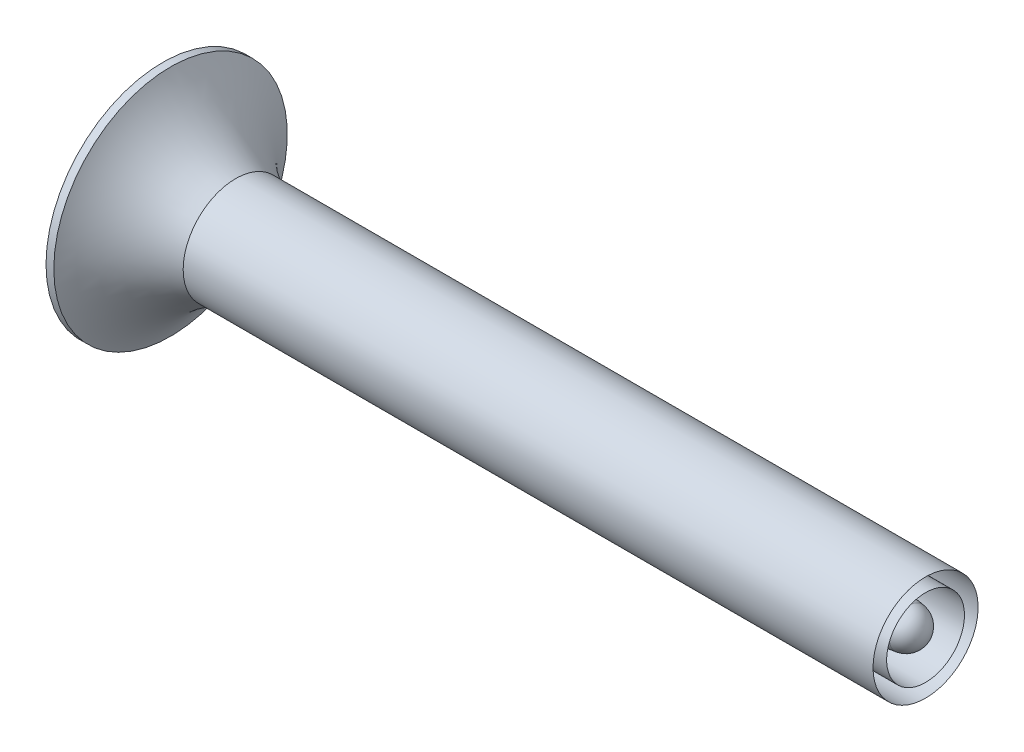
SolidWorks part; units mm, degrees
ref_plane "Front Plane" through (0, 0, 0) normal (0, 0, 1) x (1, 0, 0)
ref_plane "Top Plane" through (0, 0, 0) normal (0, 1, 0) x (1, 0, 0)
ref_plane "Right Plane" through (0, 0, 0) normal (1, 0, 0) x (0, 0, -1)
sketch "Sketch1" plane through (0, 0, 0) normal (0, 0, 1) x (1, 0, 0)
  line L0 (0, -3.81) -> (0, 0)
  line L1 (0, 3.81) -> (0.254, 3.81) construction
  line L2 (0.254, 3.81) -> (1.524, 2.54) construction
  line L3 (1.524, 2.54) -> (4.318, 1.27) construction
  line L4 (4.318, 1.27) -> (4.318, -1.27) construction
  line L5 (4.318, -1.27) -> (1.524, -2.54) construction
  line L6 (1.524, -2.54) -> (0.254, -3.81) construction
  line L7 (0.254, -3.81) -> (0, -3.81)
  line L8 (0.254, 3.81) -> (0.254, -3.81) construction
  line L9 (1.524, 2.54) -> (1.524, -2.54) construction
  line L10 (0, 0) -> (24.257, 0) construction
  line L11 (4.318, 1.27) -> (19.4753, 1.27) construction
  line L12 (4.318, -1.27) -> (19.4753, -1.27)
  line L13 (19.4753, -1.27) -> (24.3399, -0.6296)
  line L14 (24.3399, 0.6296) -> (19.4753, 1.27) construction
  line L15 (19.4753, 1.27) -> (19.4753, -1.27) construction
  line L16 (24.3399, -0.6296) -> (29.1219, 0) construction
  line L17 (29.1219, 0) -> (24.3399, 0.6296) construction
  line L18 (0, 0) -> (24.892, 0)
  line L19 (0, 0) -> (0, 3.81) construction
  arc A0 (24.892, 0) -> (24.3399, -0.6296) centre (24.257, 0) cw
  arc A1 (24.3399, 0.6296) -> (24.892, 0) centre (24.257, 0) cw construction
  arc A2 (4.318, -1.27) -> (0.254, -3.81) centre (4.318, -5.7912) ccw
  point P14 (4.318, 0)
  point P26 (23.5984, -1.4211)
  point P27 (0, 0)
  point P28 (0, 0)
  point P29 (23.5984, -1.27)
  point P30 (24.1721, -1.27)
  point P31 (0, 0)
  point P32 (26.9794, -1.27)
  point P33 (0, 0)
  point P34 (0, 0)
  point P35 (0, 0)
  point P36 (0, 0)
  point P37 (0, 0)
  point P38 (0, 0)
  point P39 (0, 0)
  point P40 (0, 0)
  point P41 (0, 0)
  point P42 (0, 0)
  point P43 (0, 0)
  point P44 (0, 0)
  point P45 (0, 0)
  point P46 (0, 0)
  point P47 (0, 0)
  point P48 (0, 0)
  point P49 (0, 0)
  point P50 (0, 0)
  point P51 (0, 0)
  dimension "D10" = 0.635
  dimension "D1" = 7.62
  dimension "D2" = 4.064
  dimension "D3" = 45
  dimension "D4" = 45
  dimension "D5" = 5.08
  dimension "D6" = 2.54
  dimension "D7" = 4.318
  dimension "D8" = 24.892
  dimension "D9" = 15
revolve "Revolve1" add sketch "Sketch1" angle 360 about L18
sketch "Sketch2" plane through (0, 0, 0) normal (1, 0, 0) x (0, 0, -1)
  circle A1 centre (0, 0) radius 1.27
  circle A3 centre (0, 0) radius 1.27 construction
surface "Max Pre-Drill Diameter" sketch "Sketch2"
sketch "Sketch3" plane through (0, 0, 0) normal (-1, 0, 0) x (0, 0, 1)
  circle A0 centre (0, 0) radius 1.7145
  dimension "D1" = 3.429
surface "Thread Diameter" sketch "Sketch3"
